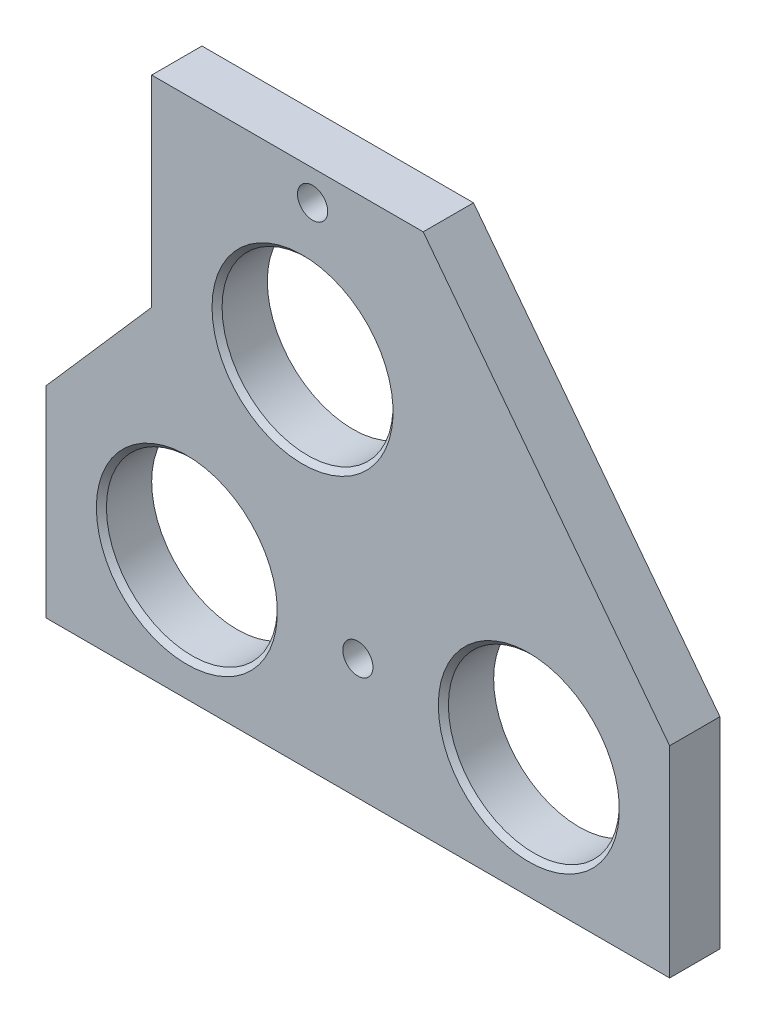
SolidWorks part; units mm, degrees
material "Stop 1060"
ref_plane "Płaszczyzna przednia" through (0, 0, 0) normal (0, 0, 1) x (1, 0, 0)
ref_plane "Płaszczyzna górna" through (0, 0, 0) normal (0, 1, 0) x (1, 0, 0)
ref_plane "Płaszczyzna prawa" through (0, 0, 0) normal (1, 0, 0) x (0, 0, -1)
sketch "Szkic1" plane through (0, 0, 0) normal (0, 0, 1) x (1, 0, 0)
  line L0 (-14, -12) -> (-14, 8)
  line L1 (-3.5, 40) -> (23.5, 40)
  line L2 (48, 8) -> (48, -12)
  line L3 (48, -12) -> (-14, -12)
  line L4 (-3.5, 40) -> (-3.5, 20)
  line L6 (-14, 8) -> (-3.5, 20)
  line L7 (23.5, 40) -> (48, 8)
  circle A0 centre (0, 0) radius 8.5
  circle A1 centre (34, 0) radius 8.5
  circle A2 centre (11.5, 23) radius 8.5
  circle A3 centre (12.5, 37) radius 1.5
  circle A4 centre (17, 0) radius 1.5
  dimension "D1" = 17
  dimension "D2" = 17
  dimension "D3" = 17
  dimension "D4" = 34
  dimension "D5" = 23
  dimension "D6" = 11.5
  dimension "D8" = 14
  dimension "D9" = 14
  dimension "D10" = 3
  dimension "D11" = 12
  dimension "D17" = 3
  dimension "D18" = 16
  dimension "D19" = 3
  dimension "D20" = 17
  dimension "D21" = 23
  dimension "3" = 3
  dimension "D7" = 12
  dimension "D12" = 20
  dimension "D13" = 27
  dimension "D14" = 20
  dimension "D15" = 20
  dimension "D16" = 24.5
extrude "Dodanie-wyciągnięcie1" add sketch "Szkic1" along normal blind 5
chamfer "Sfazowanie2" distance 0.5 angle 45 3 edges at (42.5, 0, 5) (20, 23, 5) (8.5, 0, 5)
